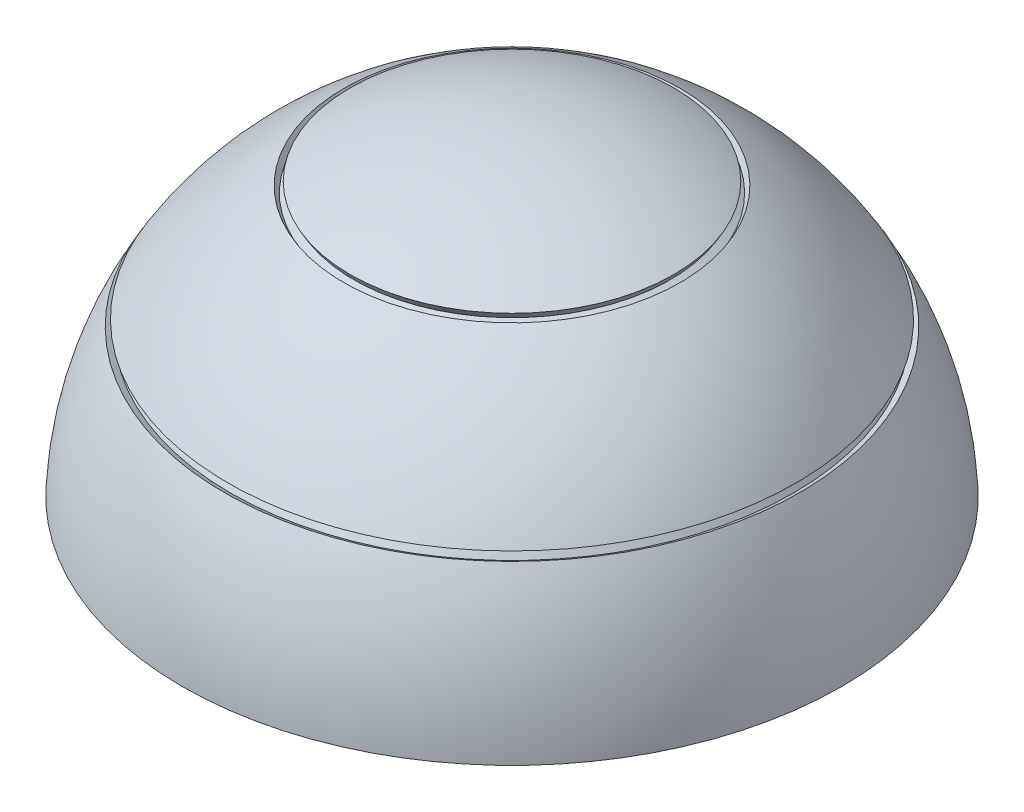
SolidWorks part; units mm, degrees
ref_plane "Front Plane" through (0, 0, 0) normal (0, 0, 1) x (1, 0, 0)
ref_plane "Top Plane" through (0, 0, 0) normal (0, 1, 0) x (1, 0, 0)
ref_plane "Right Plane" through (0, 0, 0) normal (1, 0, 0) x (0, 0, -1)
sketch "Sketch1" plane through (0, 0, 0) normal (0, 1, 0) x (1, 0, 0)
  line L0 (0, -44.45) -> (0, 44.45)
  arc A0 (0, 44.45) -> (0, -44.45) centre (0, 0) ccw
  arc A1 (0, 42.45) -> (0, -42.45) centre (0, 0) ccw
  circle A3 centre (0, 0) radius 44.45 construction
  circle A4 centre (0, 0) radius 42.45 construction
  point P1 (42.45, 0)
  point P6 (42.5077, 12.9959)
  dimension "D1" = 88.9
  dimension "D2" = 2
revolve "Revolve1" add sketch "Sketch1" angle 180 about L0
sketch "Sketch2" plane through (0, 0, 0) normal (0, 1, 0) x (1, 0, 0)
  circle A0 centre (0, 0) radius 44.45
extrude "Cut-Extrude1" cut sketch "Sketch2" along normal blind 2
sketch "30deg" plane through (0, 0, 0) normal (1, 0, 0) x (0, 0, -1)
  line L0 (-1000, 0) -> (49000, 0) construction
  line L1 (0, 0) -> (43.45, 0)
  line L2 (44.45, 0.5) -> (43.45, 0.5)
  line L3 (43.45, 0.5) -> (43.45, -0.5)
  line L4 (43.45, -0.5) -> (44.45, -0.5)
  line L5 (44.45, 0.5) -> (44.45, -0.5)
  line L6 (38.2448, 22.658) -> (37.3788, 22.158)
  line L7 (0, 0) -> (-44.45, 0)
  line L8 (0, 0) -> (44.45, 0) construction
  line L9 (37.3788, 22.158) -> (37.8788, 21.292)
  line L10 (0, 0) -> (-38.4948, 22.225) [skipped]
  line L11 (0, 0) -> (-22.225, 38.4948) [skipped]
  line L12 (0, 0) -> (38.4948, 22.225) [skipped]
  line L13 (0, 0) -> (22.225, 38.4948) [skipped]
  line L14 (0, 0) -> (0, 44.45) [skipped]
  line L15 (37.8788, 21.292) -> (38.7448, 21.792)
  line L16 (38.2448, 22.658) -> (38.7448, 21.792)
  line L17 (0, 0) -> (37.6288, 21.725)
  line L18 (21.792, 38.7448) -> (21.292, 37.8788)
  line L19 (21.292, 37.8788) -> (22.158, 37.3788)
  line L20 (22.158, 37.3788) -> (22.658, 38.2448)
  line L21 (21.792, 38.7448) -> (22.658, 38.2448)
  line L22 (0, 0) -> (21.725, 37.6288)
  line L23 (0, 0) -> (43.45, 0) construction
  line L24 (0, 0) -> (37.6288, 21.725) construction
  line L25 (0, -1000) -> (0, 49000) construction
  arc A1 (44.405, 2) -> (-44.405, 2) centre (0, 0) ccw construction
  point P14 (44.45, 0)
  point P29 (38.4948, 22.225)
  point P35 (22.225, 38.4948)
  dimension "D2" = 1
  dimension "D3" = 1
  dimension "D5" = 30
  dimension "D1" = 7
  dimension "D4" = 3
revolve "Cut-Revolve1" cut sketch "30deg" angle 360 about L25
sketch "Sketch4" plane through (0, 0, 0) normal (0, 1, 0) x (1, 0, 0)
  line L0 (0, 0) -> (0, 43.45)
  line L1 (0.5, 44.45) -> (-0.5, 44.45)
  line L2 (-0.5, 43.45) -> (0.5, 43.45)
  line L3 (-0.5, 43.45) -> (-0.5, 44.45)
  line L4 (0.5, 43.45) -> (0.5, 44.45)
  line L5 (0, 0) -> (21.725, 37.6288)
  line L6 (21.292, 37.8788) -> (21.792, 38.7448)
  line L7 (21.292, 37.8788) -> (22.158, 37.3788)
  line L8 (22.158, 37.3788) -> (22.658, 38.2448)
  line L9 (22.658, 38.2448) -> (21.792, 38.7448)
  line L10 (0, 0) -> (37.6288, 21.725)
  line L11 (37.3788, 22.158) -> (38.2448, 22.658)
  line L12 (37.3788, 22.158) -> (37.8788, 21.292)
  line L13 (37.8788, 21.292) -> (38.7448, 21.792)
  line L14 (38.7448, 21.792) -> (38.2448, 22.658)
  line L15 (0, 0) -> (43.45, 0)
  line L16 (43.45, 0.5) -> (44.45, 0.5)
  line L17 (43.45, 0.5) -> (43.45, -0.5)
  line L18 (43.45, -0.5) -> (44.45, -0.5)
  line L19 (44.45, -0.5) -> (44.45, 0.5)
  line L20 (0, 0) -> (37.6288, -21.725)
  line L21 (37.8788, -21.292) -> (38.7448, -21.792)
  line L22 (37.8788, -21.292) -> (37.3788, -22.158)
  line L23 (37.3788, -22.158) -> (38.2448, -22.658)
  line L24 (38.2448, -22.658) -> (38.7448, -21.792)
  line L25 (0, 0) -> (21.725, -37.6288)
  line L26 (22.158, -37.3788) -> (22.658, -38.2448)
  line L27 (22.158, -37.3788) -> (21.292, -37.8788)
  line L28 (21.292, -37.8788) -> (21.792, -38.7448)
  line L29 (21.792, -38.7448) -> (22.658, -38.2448)
  line L30 (0, 0) -> (0, -43.45)
  line L31 (0.5, -43.45) -> (0.5, -44.45)
  line L32 (0.5, -43.45) -> (-0.5, -43.45)
  line L33 (-0.5, -43.45) -> (-0.5, -44.45)
  line L34 (-0.5, -44.45) -> (0.5, -44.45)
  line L35 (0, 0) -> (-21.725, -37.6288)
  line L36 (-21.292, -37.8788) -> (-21.792, -38.7448)
  line L37 (-21.292, -37.8788) -> (-22.158, -37.3788)
  line L38 (-22.158, -37.3788) -> (-22.658, -38.2448)
  line L39 (-22.658, -38.2448) -> (-21.792, -38.7448)
  line L40 (0, 0) -> (-37.6288, -21.725)
  line L41 (-37.3788, -22.158) -> (-38.2448, -22.658)
  line L42 (-37.3788, -22.158) -> (-37.8788, -21.292)
  line L43 (-37.8788, -21.292) -> (-38.7448, -21.792)
  line L44 (-38.7448, -21.792) -> (-38.2448, -22.658)
  line L45 (0, 0) -> (-43.45, 0)
  line L46 (-43.45, -0.5) -> (-44.45, -0.5)
  line L47 (-43.45, -0.5) -> (-43.45, 0.5)
  line L48 (-43.45, 0.5) -> (-44.45, 0.5)
  line L49 (-44.45, 0.5) -> (-44.45, -0.5)
  line L50 (0, 0) -> (-37.6288, 21.725)
  line L51 (-37.8788, 21.292) -> (-38.7448, 21.792)
  line L52 (-37.8788, 21.292) -> (-37.3788, 22.158)
  line L53 (-37.3788, 22.158) -> (-38.2448, 22.658)
  line L54 (-38.2448, 22.658) -> (-38.7448, 21.792)
  line L55 (0, 0) -> (-21.725, 37.6288)
  line L56 (-22.158, 37.3788) -> (-22.658, 38.2448)
  line L57 (-22.158, 37.3788) -> (-21.292, 37.8788)
  line L58 (-21.292, 37.8788) -> (-21.792, 38.7448)
  line L59 (-21.792, 38.7448) -> (-22.658, 38.2448)
  line L60 (0, 0) -> (0, 43.45) construction
  line L61 (0, 0) -> (21.725, 37.6288) construction
  circle A0 centre (0, 0) radius 44.45 construction
  point P7 (0, 44.45)
  point P10 (0, 43.45)
  dimension "D1" = 88.9
  dimension "D2" = 1
  dimension "D3" = 1
  dimension "D5" = 30
  dimension "D4" = 12
ref_plane "Plane1" through (0, 44.45, 0) normal (0, 1, 0) x (1, 0, 0)
sketch "Sketch5" plane through (0, 44.45, 0) normal (0, 1, 0) x (1, 0, 0)
  circle A0 centre (0, 0) radius 0.5
  dimension "D1" = 1
